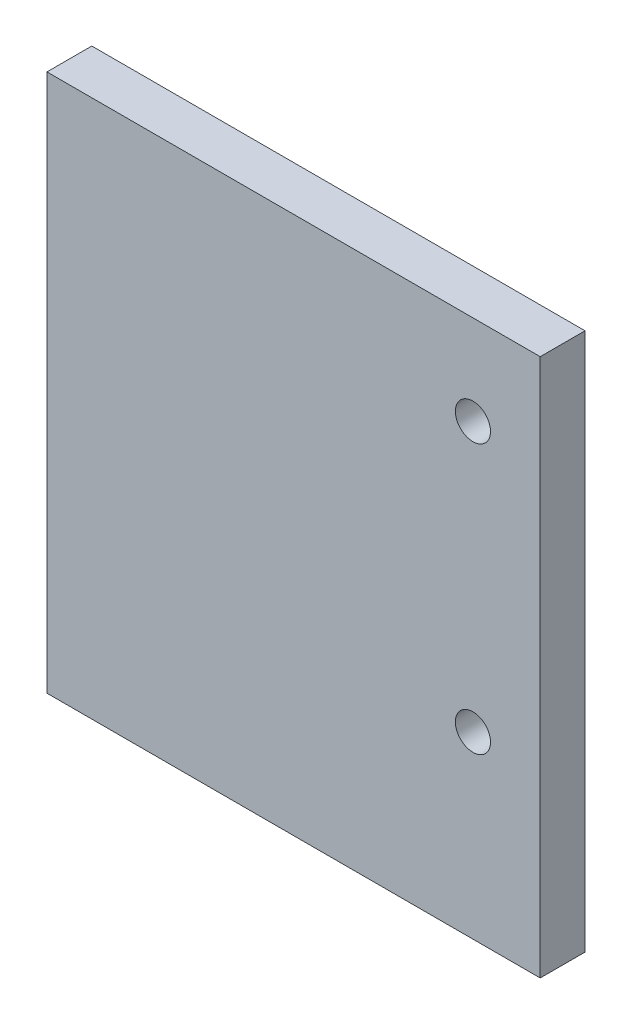
SolidWorks part; units mm, degrees
material "6061 Alloy"
ref_plane "X-Y Datum" through (0, 0, 0) normal (0, 0, 1) x (1, 0, 0)
ref_plane "X-Z Datum" through (0, 0, 0) normal (0, 1, 0) x (1, 0, 0)
ref_plane "Y-Z Datum" through (0, 0, 0) normal (1, 0, 0) x (0, 0, -1)
sketch "Sketch1" plane through (0, 0, 0) normal (0, 0, 1) x (1, 0, 0)
  line L1 (-34.925, 38.1) -> (34.925, 38.1)
  line L2 (-34.925, 38.1) -> (-34.925, -38.1)
  line L3 (-34.925, -38.1) -> (34.925, -38.1)
  line L4 (34.925, 38.1) -> (34.925, -38.1)
  circle A0 centre (25.4, 25.4) radius 2.4892
  circle A1 centre (25.4, -12.7) radius 2.4892
  point P4 (34.925, 0)
  point P6 (0, 38.1)
  dimension "D3" = 4.9784
  dimension "D1" = 69.85
  dimension "D2" = 76.2
  dimension "D4" = 25.4
  dimension "D5" = 9.525
  dimension "D6" = 12.7
  dimension "D7" = 9.525
extrude "Boss-Extrude1" add sketch "Sketch1" along normal mid plane 6.35
